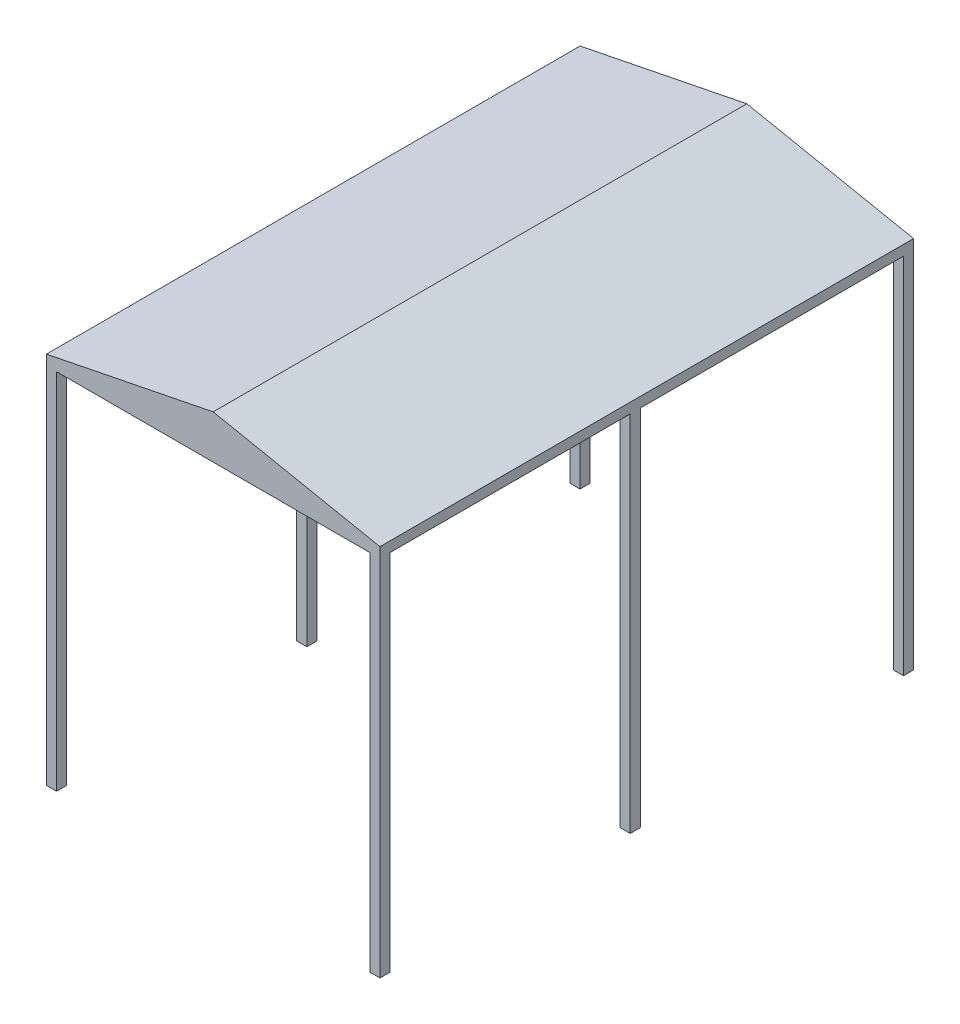
SolidWorks part; units mm, degrees
ref_plane "Alzado" through (0, 0, 0) normal (0, 0, 1) x (1, 0, 0)
ref_plane "Planta" through (0, 0, 0) normal (0, 1, 0) x (1, 0, 0)
ref_plane "Vista lateral" through (0, 0, 0) normal (1, 0, 0) x (0, 0, -1)
sketch "Croquis1" plane through (0, 0, 0) normal (0, 0, 1) x (1, 0, 0)
  line L1 (0, 0) -> (2500, 0)
  line L2 (0, 0) -> (0, 2800)
  line L3 (0, 2800) -> (2500, 2800)
  line L4 (2500, 0) -> (2500, 2800)
  dimension "D1" = 2500
  dimension "D2" = 2800
extrude "Saliente-Extruir1" add sketch "Croquis1" along normal blind 4000
sketch "Croquis2" plane through (0, 0, 0) normal (0, -1, 0) x (1, 0, 0)
  line L1 (76.2, 4000) -> (76.2, 3923.8)
  line L2 (0, 4000) -> (2500, 4000) construction
  line L3 (76.2, 3923.8) -> (0, 3923.8)
  line L4 (0, 4000) -> (0, 0) construction
  line L6 (0, 3923.8) -> (0, 2123.8)
  line L7 (0, 2123.8) -> (76.2, 2123.8)
  line L8 (76.2, 2123.8) -> (76.2, 2047.6)
  line L9 (76.2, 2047.6) -> (2423.8, 2047.6)
  line L10 (2423.8, 2047.6) -> (2423.8, 2123.8)
  line L11 (76.2, 4000) -> (2423.8, 4000)
  line L12 (2423.8, 4000) -> (2423.8, 3923.8)
  line L13 (2423.8, 3923.8) -> (2500, 3923.8)
  line L14 (2500, 4000) -> (2500, 0) construction
  line L15 (2500, 3923.8) -> (2500, 2123.8)
  line L16 (2500, 2123.8) -> (2423.8, 2123.8)
  dimension "D1" = 76.2
  dimension "D2" = 76.2
  dimension "D3" = 76.2
  dimension "D4" = 76.2
  dimension "D5" = 76.2
  dimension "D6" = 76.2
  dimension "D7" = 76.2
  dimension "D8" = 76.2
  dimension "D9" = 1800
extrude "Cortar-Extruir1" cut sketch "Croquis2" against normal blind 2723.8
sketch "Croquis3" plane through (0, 0, 0) normal (0, -1, 0) x (1, 0, 0)
  line L0 (0, 76.2) -> (76.2, 76.2)
  line L1 (0, 2123.8) -> (0, 0) construction
  line L2 (76.2, 76.2) -> (76.2, 0)
  line L3 (0, 0) -> (2500, 0) construction
  line L4 (76.2, 0) -> (2423.8, 0)
  line L5 (2423.8, 0) -> (2423.8, 76.2)
  line L6 (2423.8, 76.2) -> (2500, 76.2)
  line L7 (2500, 2123.8) -> (2500, 0) construction
  line L8 (2500, 76.2) -> (2500, 2047.6)
  line L9 (2500, 2047.6) -> (0, 2047.6)
  line L10 (0, 2047.6) -> (0, 76.2)
  dimension "D1" = 76.2
  dimension "D2" = 76.2
  dimension "D3" = 76.2
  dimension "D4" = 76.2
extrude "Cortar-Extruir2" cut sketch "Croquis3" against normal blind 2723.8
sketch "Croquis4" plane through (0, 0, 0) normal (0, 0, -1) x (-1, 0, 0)
  line L0 (-2500, 2800) -> (-1250, 3050)
  line L1 (-1250, 3050) -> (0, 2800)
  line L2 (-2500, 2800) -> (0, 2800) construction
  line L3 (-2500, 2800) -> (0, 2800)
  point P7 (-1250, 2800)
  dimension "D1" = 250
extrude "Saliente-Extruir2" add sketch "Croquis4" against normal up to surface (4000 mm away) up to face at (1250, 1380.95, 4000)
